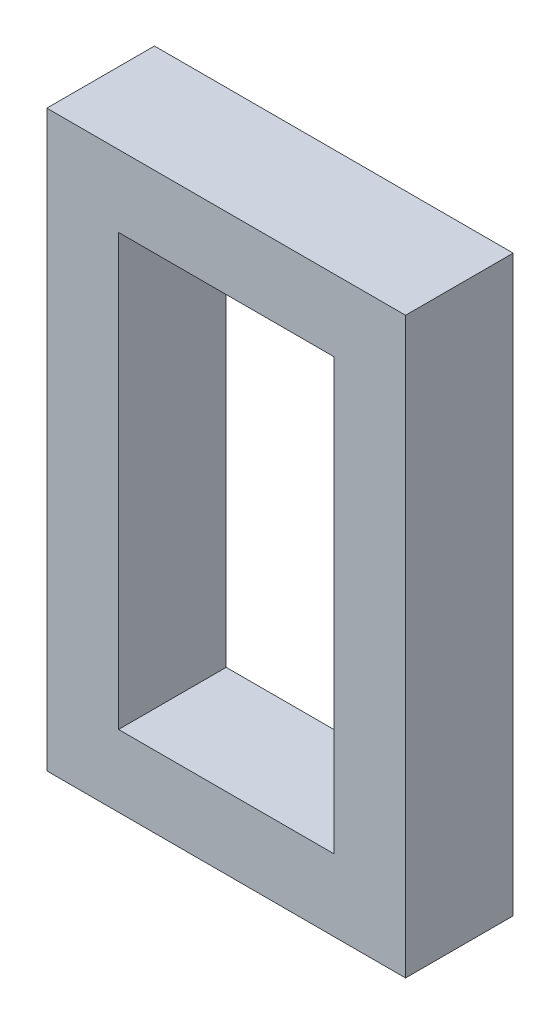
SolidWorks part; units mm, degrees
ref_plane "Front Plane" through (0, 0, 0) normal (0, 0, 1) x (1, 0, 0)
ref_plane "Top Plane" through (0, 0, 0) normal (0, 1, 0) x (1, 0, 0)
ref_plane "Right Plane" through (0, 0, 0) normal (1, 0, 0) x (0, 0, -1)
sketch "Sketch1" plane through (0, 0, 0) normal (0, 0, 1) x (1, 0, 0)
  line L1 (0, 0) -> (10, 0)
  line L2 (0, 0) -> (0, 16)
  line L3 (0, 16) -> (10, 16)
  line L4 (10, 0) -> (10, 16)
  line L6 (2, 2) -> (8, 2)
  line L7 (2, 2) -> (2, 14)
  line L8 (2, 14) -> (8, 14)
  line L9 (8, 2) -> (8, 14)
  dimension "D1" = 2
  dimension "D2" = 8
  dimension "D3" = 10
  dimension "D4" = 2
  dimension "D5" = 14
  dimension "D6" = 16
extrude "Profile" add sketch "Sketch1" along normal blind 3
equation "\"Profile_Depth\" = 3mm"
equation "\"D1@Profile\" = \"Profile_Depth\""
equation "\"Profile_Sketch_1\" = 2mm"
equation "\"D1@Sketch1\" = \"Profile_Sketch_1\""
equation "\"Profile_Sketch_2\" = 8mm"
equation "\"D2@Sketch1\" = \"Profile_Sketch_2\""
equation "\"Profile_Sketch_3\" = 10mm"
equation "\"D3@Sketch1\" = \"Profile_Sketch_3\""
equation "\"Profile_Sketch_4\" = 2mm"
equation "\"D4@Sketch1\" = \"Profile_Sketch_4\""
equation "\"Profile_Sketch_5\" = 14mm"
equation "\"D5@Sketch1\" = \"Profile_Sketch_5\""
equation "\"Profile_Sketch_6\" = 16mm"
equation "\"D6@Sketch1\" = \"Profile_Sketch_6\""
equation "\"EnvelopeWidth\" = 10mm"
equation "\"EnvelopeHeight\" = 16mm"
